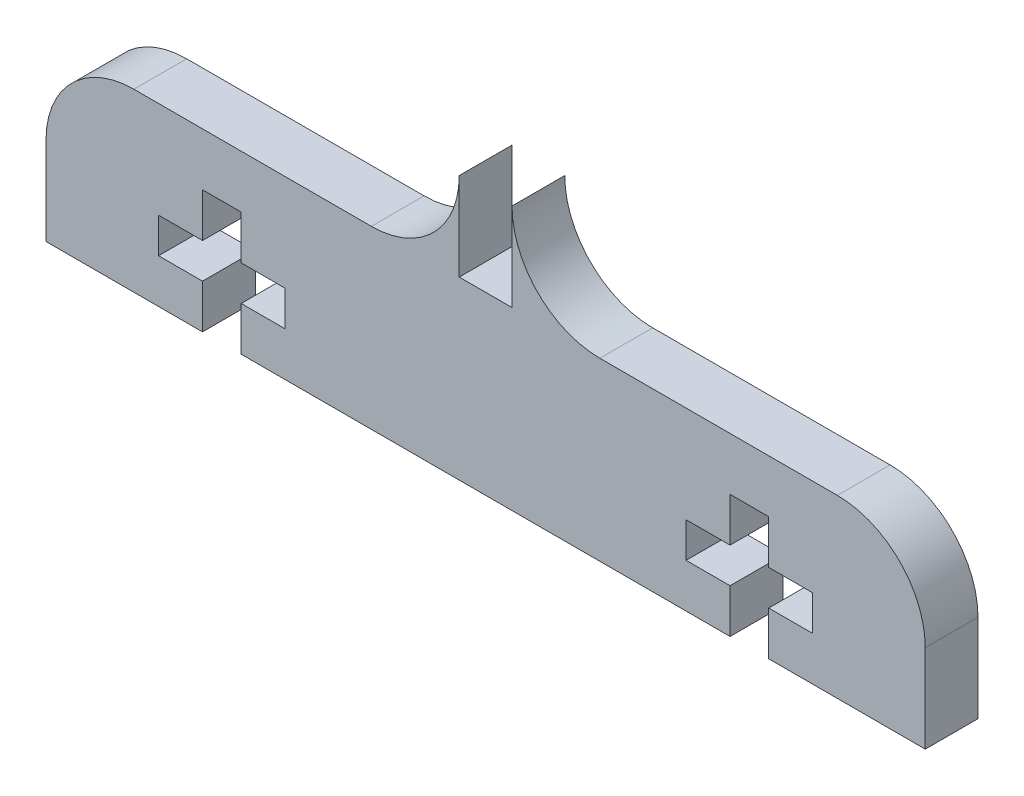
SolidWorks part; units mm, degrees
ref_plane "Front Plane" through (0, 0, 0) normal (0, 0, 1) x (1, 0, 0)
ref_plane "Top Plane" through (0, 0, 0) normal (0, 1, 0) x (1, 0, 0)
ref_plane "Right Plane" through (0, 0, 0) normal (1, 0, 0) x (0, 0, -1)
sketch "Sketch1" plane through (0, 0, 0) normal (0, 0, 1) x (1, 0, 0)
  line L0 (-15, 5) -> (-15, -5) construction
  line L1 (-25, -5) -> (-16.1, -5)
  line L2 (-25, -5) -> (-25, 5)
  line L3 (-25, 5) -> (-6.5, 5)
  line L4 (25, -5) -> (25, 5)
  line L5 (-25, -5) -> (25, 5) construction
  line L6 (-25, 5) -> (25, -5) construction
  line L7 (0, 5) -> (0, -5) construction
  line L8 (-16.1, -5) -> (-16.1, -2.5)
  line L9 (-16.1, -2.5) -> (-18.6, -2.5)
  line L10 (-18.6, -2.5) -> (-18.6, -0.5)
  line L11 (-18.6, -0.5) -> (-16.1, -0.5)
  line L12 (-16.1, -0.5) -> (-16.1, 2)
  line L13 (-16.1, 2) -> (-13.9, 2)
  line L14 (-13.9, 2) -> (-13.9, -0.5)
  line L15 (-13.9, -0.5) -> (-11.4, -0.5)
  line L16 (-11.4, -0.5) -> (-11.4, -2.5)
  line L17 (-11.4, -2.5) -> (-13.9, -2.5)
  line L18 (-13.9, -2.5) -> (-13.9, -5)
  line L19 (13.9, -2.5) -> (13.9, -5)
  line L20 (11.4, -2.5) -> (13.9, -2.5)
  line L21 (11.4, -0.5) -> (11.4, -2.5)
  line L22 (13.9, -0.5) -> (11.4, -0.5)
  line L23 (13.9, 2) -> (13.9, -0.5)
  line L24 (15, 5) -> (15, -5) construction
  line L25 (16.1, 2) -> (13.9, 2)
  line L26 (16.1, -0.5) -> (16.1, 2)
  line L27 (18.6, -0.5) -> (16.1, -0.5)
  line L28 (18.6, -2.5) -> (18.6, -0.5)
  line L29 (16.1, -2.5) -> (18.6, -2.5)
  line L30 (16.1, -5) -> (16.1, -2.5)
  line L31 (-13.9, -5) -> (13.9, -5)
  line L32 (16.1, -5) -> (25, -5)
  line L33 (-1.5, 5) -> (1.5, 5)
  line L34 (-1.5, 10) -> (-1.5, 5)
  line L35 (1.5, 10) -> (1.5, 5)
  line L36 (6.5, 5) -> (25, 5)
  arc A0 (-1.5, 10) -> (-6.5, 5) centre (-6.5, 10) cw
  arc A1 (1.5, 10) -> (6.5, 5) centre (6.5, 10) ccw
  point P0 (0, 0)
  point P22 (-15, 2)
  point P39 (0, 0)
  dimension "D11" = 5
  dimension "D1" = 50
  dimension "D2" = 10
  dimension "D3" = 10
  dimension "D4" = 2.5
  dimension "D5" = 2.5
  dimension "D6" = 2
  dimension "D7" = 2.2
  dimension "D8" = 2.5
  dimension "D9" = 2.5
  dimension "D10" = 5
  dimension "D12" = 1.5
extrude "Boss-Extrude1" add sketch "Sketch1" along normal blind 3
fillet "Fillet1" radius 5 2 edges at (25, 5, 1.5) (-25, 5, 1.5)
